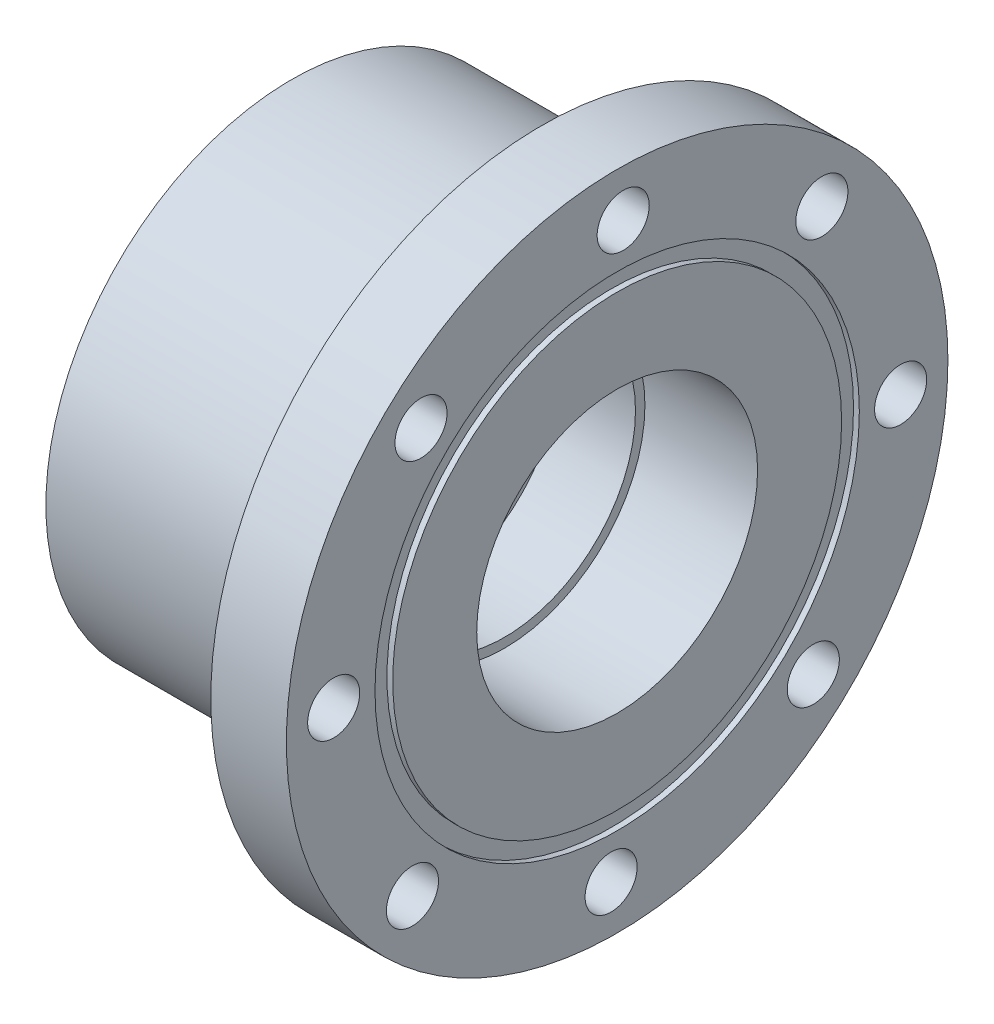
SolidWorks part; units mm, degrees
ref_plane "Front Plane" through (0, 0, 0) normal (0, 0, 1) x (1, 0, 0)
ref_plane "Top Plane" through (0, 0, 0) normal (0, 1, 0) x (1, 0, 0)
ref_plane "Right Plane" through (0, 0, 0) normal (1, 0, 0) x (0, 0, -1)
sketch "Main sketch" plane through (0, 0, 0) normal (0, 0, 1) x (1, 0, 0)
  line L0 (0, 8.5) -> (0, 20)
  line L1 (0, 20) -> (-12, 20)
  line L2 (-12, 20) -> (-12, 33.02)
  line L3 (-12, 33.02) -> (21.59, 33.02)
  line L4 (21.59, 33.02) -> (21.59, 44.45)
  line L5 (21.59, 44.45) -> (31.75, 44.45)
  line L6 (31.75, 44.45) -> (31.75, 32.5438)
  line L7 (31.75, 32.5438) -> (30.9721, 32.5438)
  line L8 (30.9721, 32.5438) -> (30.9721, 30.1625)
  line L9 (30.9721, 30.1625) -> (31.75, 30.1625)
  line L10 (31.75, 30.1625) -> (31.75, 18.8722)
  line L11 (31.75, 18.8722) -> (16.6116, 18.8722)
  line L12 (16.6116, 18.8722) -> (16.6116, 17.6022)
  line L13 (16.6116, 17.6022) -> (6.35, 17.6022)
  line L14 (6.35, 17.6022) -> (6.35, 8.5)
  line L15 (6.35, 8.5) -> (0, 8.5)
  line L16 (0, 0) -> (0, 8.5) construction
  point P18 (0, 0)
  dimension "D1" = 8.5
  dimension "D2" = 20
  dimension "D3" = 25.4
  dimension "D4" = 17.6022
  dimension "D5" = 12
  dimension "D6" = 44.45
  dimension "D7" = 18.8722
  dimension "D8" = 32.5437
  dimension "D11" = 6.35
  dimension "D12" = 10.2616
  dimension "D13" = 33.02
  dimension "D14" = 10.16
  dimension "D9" = 30.1625
  dimension "D10" = 0.7779
ref_axis "Axis1" through (71.9501, 0, 0) along (-1, 0, 0)
revolve "Revolve1" add sketch "Main sketch" angle 360 about axis through (71.9501, 0, 0) along (-1, 0, 0)
sketch "Sketch2" plane through (31.75, 0, 0) normal (1, 0, 0) x (0, 0, -1)
  circle A0 centre (0, 0) radius 38.1 construction
  point P0 (0, 0)
  point P3 (-38.0913, 0.8131)
  point P4 (-27.5096, -26.3597)
  point P7 (-0.8131, -38.0913)
  point P8 (26.3597, -27.5096)
  point P9 (38.0913, -0.8131)
  point P10 (27.5096, 26.3597)
  point P11 (0.8131, 38.0913)
  point P12 (-26.3597, 27.5096)
  point P13 (0, 0)
  point P16 (0, 0)
  dimension "D2" = 76.2
  dimension "D1" = 8
hole_wizard "M6 Clearance Hole1" positions "Sketch2" profile "Sketch3" hole size "M6" standard "ISO" end condition through all
sketch "Sketch3" plane through (31.75, 0, 0) normal (0, 1, 0) x (0, 0, -1)
  line L0 (0, 0) -> (0, 43.75)
  line L1 (0, 43.75) -> (3.5, 43.75)
  line L2 (3.5, 43.75) -> (3.5, 0)
  line L5 (3.5, 0) -> (0, 0)
  line L11 (0, -6.35) -> (0, 107.95) construction
  dimension "Thru Hole Dia." = 7
  dimension "Thru Hole Depth" = 43.75
equation "\"Shaft_OD\"= 17mm"
equation "\"O_Ring_ID\" = 2.375in"
equation "\"O_Ring_CS\"= 1 / 16in'cross section"
equation "\"Bearing_OD\"= 40mm"
equation "\"Bearing_Depth\"= 12mm"
equation "\"Stationary_Face_Seal_OD\"= 1.386in"
equation "\"Flange_Dia\"= 3.5in"
equation "\"Screw_Dia\"= 6mm"
equation "\"Screws\"= 8"
equation "\"Seal_Space\" = 1in"
equation "\"D1@Main sketch\" = \"Shaft_OD\" / 2"
equation "\"D2@Main sketch\" = \"Bearing_OD\" / 2"
equation "\"D3@Main sketch\" = \"Seal_Space\""
equation "\"D4@Main sketch\" = \"Stationary_Face_Seal_OD\" / 2"
equation "\"D5@Main sketch\" = \"Bearing_Depth\""
equation "\"D6@Main sketch\" = \"Flange_Dia\" / 2"
equation "\"Seal_Area_Dia\" = 36mm"
equation "\"D7@Main sketch\" =  ( \"Stationary_Face_Seal_OD\" / 2 )  + .05in"
equation "\"D8@Main sketch\"=\"O_Ring_ID\" / 2 + \"O_Ring_CS\" * 1.5"
equation "\"Face_Seal_Height\"=0.404"
equation "\"D12@Main sketch\" = \"Face_Seal_Height\""
equation "\"Housing_OD\"=1.3"
equation "\"D13@Main sketch\"=\"Housing_OD\""
equation "\"D10@Main sketch\"=\"O_Ring_CS\"*.49"
equation "\"D9@Main sketch\"=\"O_Ring_ID\"/2"
equation "\"D2@Sketch2\"=\"Flange_Dia\"-.50"
